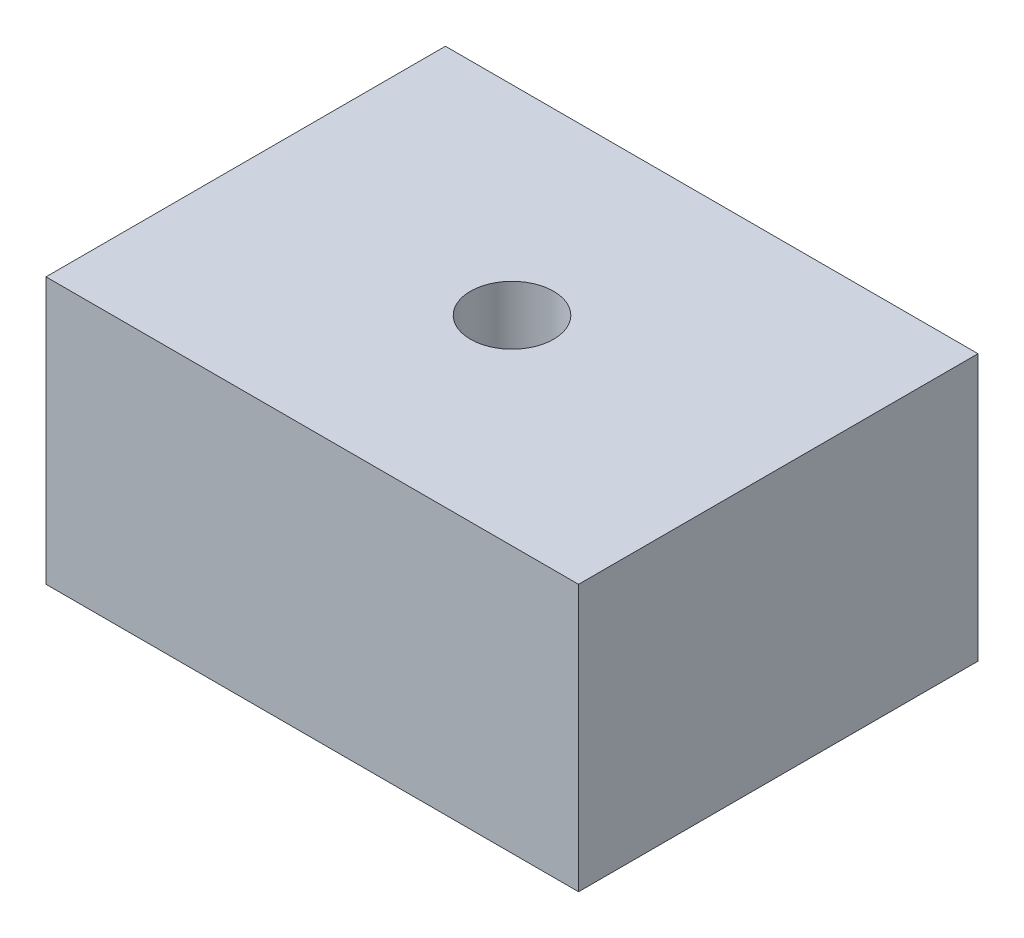
SolidWorks part; units mm, degrees
ref_plane "Front Plane" through (0, 0, 0) normal (0, 0, 1) x (1, 0, 0)
ref_plane "Top Plane" through (0, 0, 0) normal (0, 1, 0) x (1, 0, 0)
ref_plane "Right Plane" through (0, 0, 0) normal (1, 0, 0) x (0, 0, -1)
sketch "Sketch1" plane through (0, 0, 0) normal (0, 1, 0) x (1, 0, 0)
  line L1 (-50.8, 38.1) -> (0, 38.1)
  line L2 (-50.8, 38.1) -> (-50.8, 0)
  line L3 (-50.8, 0) -> (0, 0)
  line L4 (0, 38.1) -> (0, 0)
  point P4 (0, 0)
  dimension "D1" = 50.8
  dimension "D2" = 38.1
extrude "Boss-Extrude1" add sketch "Sketch1" along normal blind 25.4
hole_wizard "3/8-16 Tapped Hole1" positions "Sketch2" profile "Sketch3" tap size "3/8-16" standard "ANSI Inch" end condition through all
sketch "Sketch2" plane through (0, 25.4, 0) normal (0, 1, 0) x (1, 0, 0)
  line L0 (-50.8, 38.1) -> (-50.8, 0) construction
  line L1 (-50.8, 0) -> (0, 0) construction
  point P0 (-25.4, 19.05)
  dimension "D1" = 25.4
  dimension "D2" = 19.05
cosmetic thread "Hole Thread1"
sketch "Sketch3" plane through (-25.4, 25.4, -19.05) normal (1, 0, 0) x (0, 0, 1)
  line L0 (0, 0) -> (0, 25.4)
  line L1 (0, 25.4) -> (3.9687, 25.4)
  line L2 (3.9687, 25.4) -> (3.9687, 0)
  line L5 (3.9687, 0) -> (0, 0)
  line L11 (0, -6.35) -> (0, 107.95) construction
  dimension "Thru Tap Drill Dia." = 7.9375
  dimension "Thru Tap Drill Depth" = 25.4
